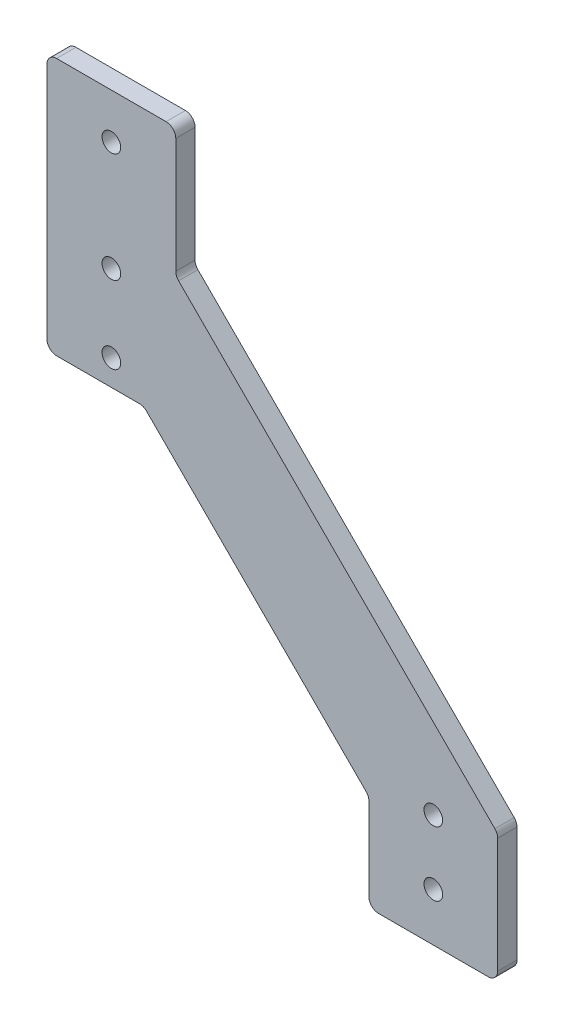
SolidWorks part; units mm, degrees
material "ABS"
ref_plane "Front Plane" through (0, 0, 0) normal (0, 0, 1) x (1, 0, 0)
ref_plane "Top Plane" through (0, 0, 0) normal (0, 1, 0) x (1, 0, 0)
ref_plane "Right Plane" through (0, 0, 0) normal (1, 0, 0) x (0, 0, -1)
sketch "Sketch1" plane through (0, 0, 0) normal (0, 0, 1) x (1, 0, 0)
  line L1 (-20, -20) -> (-5, -20)
  line L3 (0, 0) -> (50, -50)
  line L6 (30, -55) -> (30, -70)
  line L7 (30, -70) -> (50, -70)
  line L8 (50, -50) -> (50, -70)
  line L9 (-20, 0) -> (-20, -20)
  line L10 (-20, 0) -> (-20, 20)
  line L11 (-20, 20) -> (0, 20)
  line L12 (0, 0) -> (0, 20)
  line L19 (-5, -20) -> (30, -55)
  circle A0 centre (-10, -16) radius 1.45
  circle A1 centre (-10, -4) radius 1.45
  circle A2 centre (40, -52.5) radius 1.45
  circle A3 centre (40, -62.5) radius 1.45
  circle A4 centre (-10, 13) radius 1.45
  point P21 (40, -70)
  dimension "D6" = 2.9
  dimension "D7" = 2.9
  dimension "D1" = 20
  dimension "D2" = 20
  dimension "D3" = 20
  dimension "D4" = 50
  dimension "D5" = 20
  dimension "D8" = 7.5
  dimension "D9" = 10
  dimension "D10" = 4
  dimension "D11" = 20
  dimension "D12" = 20
  dimension "D13" = 15
  dimension "D14" = 12
  dimension "D15" = 7
extrude "Boss-Extrude1" add sketch "Sketch1" along normal blind 3
fillet "Fillet1" radius 1.5 9 edges at (30, -70, 1.5) (50, -70, 1.5) (-20, -20, 1.5) (0, 20, 1.5) (-20, 20, 1.5) (50, -50, 1.5) (0, 0, 1.5) (30, -55, 1.5) (-5, -20, 1.5)
